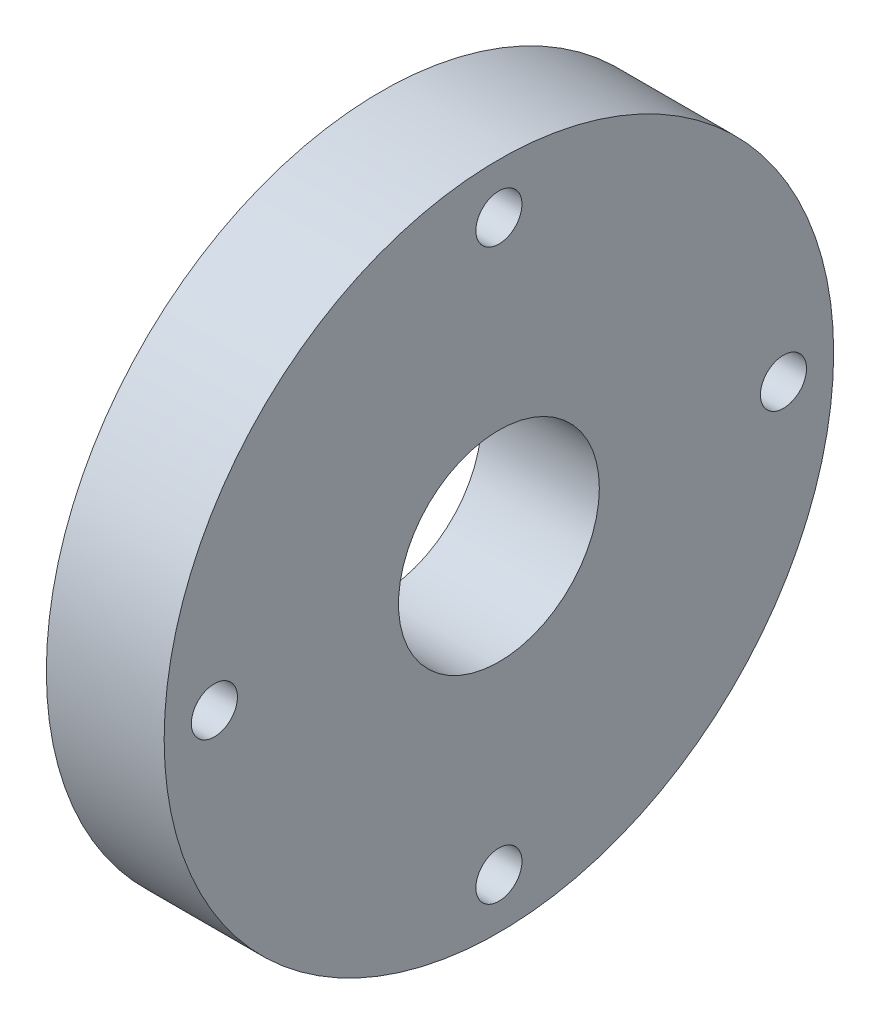
SolidWorks part; units mm, degrees
ref_plane "Front Plane" through (0, 0, 0) normal (1, 0, 0) x (0, 1, 0)
ref_plane "Top Plane" through (0, 0, 0) normal (0, 0, 1) x (0, 1, 0)
ref_plane "Right Plane" through (0, 0, 0) normal (0, 1, 0) x (-1, 0, 0)
sketch "Sketch1" plane through (0, 0, 0) normal (1, 0, 0) x (0, 1, 0)
  circle A0 centre (0, 0) radius 63.5
extrude "Boss-Extrude1" add sketch "Sketch1" along normal blind 22.352
sketch "Sketch2" plane through (0, 0, 0) normal (1, 0, 0) x (0, 1, 0)
  circle A0 centre (0, 0) radius 19.05
extrude "Cut-Extrude2" cut sketch "Sketch2" along normal through all
sketch "Sketch3" plane through (0, 0, 0) normal (1, 0, 0) x (0, 1, 0)
  circle A0 centre (53.975, 0) radius 4.3688
  circle A1 centre (0, 53.975) radius 4.3688
  circle A2 centre (-53.975, 0) radius 4.3688
  circle A3 centre (0, -53.975) radius 4.3688
extrude "Cut-Extrude4" cut sketch "Sketch3" along normal through all
sketch "Sketch4" plane through (0, 0, 0) normal (1, 0, 0) x (0, 1, 0)
  circle A0 centre (53.975, 0) radius 6.7437
  circle A1 centre (0, 53.975) radius 6.7437
  circle A2 centre (-53.975, 0) radius 6.7437
  circle A3 centre (0, -53.975) radius 6.7437
extrude "Cut-Extrude5" cut sketch "Sketch4" along normal blind 9.652
